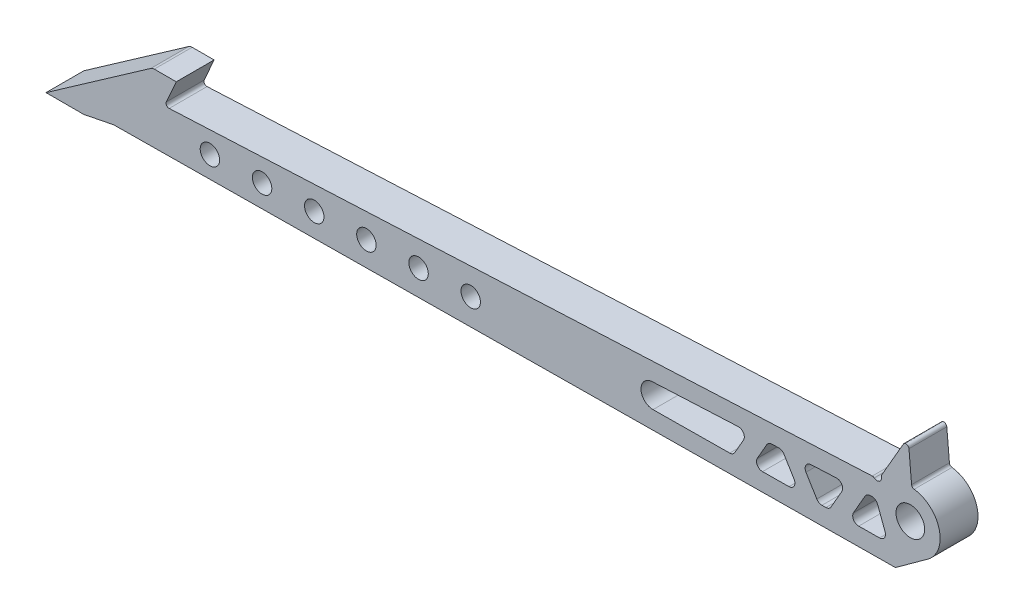
SolidWorks part; units mm, degrees
material "AISI 4340 Steel, normalized"
ref_plane "Front Plane" through (0, 0, 0) normal (0, 0, 1) x (1, 0, 0)
ref_plane "Top Plane" through (0, 0, 0) normal (0, 1, 0) x (1, 0, 0)
ref_plane "Right Plane" through (0, 0, 0) normal (1, 0, 0) x (0, 0, -1)
sketch "Sketch1" plane through (0, 0, 0) normal (0, 0, 1) x (1, 0, 0)
  line L0 (-254.1014, 66.7622) -> (-244.1014, 68.7622)
  line L1 (-254.1014, 66.7622) -> (-266.8014, 66.7622)
  line L2 (-266.8014, 66.7622) -> (-231.0977, 91.7622)
  line L3 (-231.0977, 91.7622) -> (-223.0977, 91.7622)
  line L4 (-223.0977, 91.7622) -> (-227.0977, 82.7622)
  line L5 (-63.3598, 84.4827) -> (11.6902, 88.0244)
  line L6 (-244.1014, 68.7622) -> (18.1986, 71.2622)
  line L7 (18.1986, 71.2622) -> (29.0674, 79.1405)
  line L8 (16.0571, 94.2372) -> (-227.0977, 82.7622)
  line L9 (12.547, 94.0715) -> (22.4576, 111.2372)
  line L10 (11.6902, 88.0244) -> (15.7326, 77.239)
  line L11 (15.7326, 77.239) -> (-63.1331, 76.4873)
  line L12 (22.4576, 111.2372) -> (23.6835, 97.2254)
  line L13 (22.7176, 112.6875) -> (30.656, 126.4372) construction
  line L14 (84.9758, 66.7622) -> (-105.9511, 66.7622) construction
  line L15 (-211.8014, 76.277) -> (-194.3014, 76.7727)
  line L16 (-211.8014, 69.07) -> (-211.8014, 83.4841) construction
  line L17 (-194.3014, 76.7727) -> (-176.8014, 77.2684)
  line L18 (-176.8014, 77.2684) -> (-159.3014, 77.7641)
  line L19 (-159.3014, 77.7641) -> (-141.8014, 78.2598)
  line L20 (-194.3014, 76.7727) -> (-176.8014, 77.2684)
  line L21 (-176.8014, 77.2684) -> (-159.3014, 77.7641)
  line L22 (-159.3014, 77.7641) -> (-141.8014, 78.2598)
  line L23 (-141.8014, 78.2598) -> (-124.3014, 78.7555)
  circle A0 centre (23.1986, 87.2372) radius 10
  circle A1 centre (23.1986, 87.2372) radius 4.8025
  arc A2 (-63.1331, 76.4873) -> (-63.3598, 84.4827) centre (-63.1713, 80.4871) cw
  circle A3 centre (-211.8014, 76.277) radius 3.2639
  circle A4 centre (-176.8014, 77.2684) radius 3.2639
  circle A5 centre (-141.8014, 78.2598) radius 3.2639
  circle A6 centre (-194.3014, 76.7727) radius 3.2639
  circle A7 centre (-159.3014, 77.7641) radius 3.2639
  circle A8 centre (-124.3014, 78.7555) radius 3.2639
  point P33 (-211.8014, 76.277)
  dimension "D1" = 20
  dimension "D19" = 4
  dimension "D20" = 6.5278
  dimension "D28" = 9.605
  dimension "D2" = 12.7
  dimension "D3" = 35
  dimension "D4" = 290
  dimension "D5" = 8
  dimension "D6" = 2
  dimension "D7" = 25
  dimension "D8" = 4
  dimension "D9" = 14
  dimension "D10" = 5
  dimension "D11" = 6
  dimension "D12" = 6
  dimension "D13" = 70
  dimension "D14" = 10.5
  dimension "D15" = 1
  dimension "D16" = 10
  dimension "D17" = 35
  dimension "D18" = 24
  dimension "D21" = 55
  dimension "D22" = 125
  dimension "D23" = 4.5
  dimension "D24" = 7
  dimension "D25" = 66.7622
  dimension "D26" = 87.2372
  dimension "D27" = 23.1986
extrude "Boss-Extrude1" add sketch "Sketch1" along normal blind 12.7
sketch "Sketch2" plane through (0, 0, 12.7) normal (0, 0, 1) x (1, 0, 0)
  line L0 (12.547, 94.0715) -> (12.0276, 94.9261) construction
  line L1 (12.547, 94.0715) -> (-227.0977, 82.7622) construction
  line L2 (12.547, 94.0715) -> (22.4576, 111.2372) construction
  line L3 (12.547, 94.0715) -> (-227.0977, 82.7622) construction
  line L4 (12.547, 94.0715) -> (22.4576, 111.2372) construction
  circle A0 centre (12.0276, 94.9261) radius 1.5
  dimension "D2" = 3
  dimension "D1" = 1
  dimension "D3" = 122.702
  dimension "D4" = 61.409
extrude "Cut-Extrude1" cut sketch "Sketch2" against normal through all
sketch "Sketch3" plane through (0, 0, 12.7) normal (0, 0, 1) x (1, 0, 0)
  line L0 (5.2912, 87.7224) -> (-0.8014, 77.0814)
  line L1 (-10.801, 76.9861) -> (-16.6947, 86.6849)
  line L2 (-10.801, 76.9861) -> (-8.7237, 73.5677)
  line L3 (-0.8014, 77.0814) -> (-2.2921, 74.4779)
  line L4 (5.2912, 87.7224) -> (6.7818, 90.3259)
  line L5 (-16.6947, 86.6849) -> (-18.772, 90.1032)
  line L6 (-27.6947, 86.1658) -> (-33.0722, 76.7738)
  line L7 (-33.0722, 76.7738) -> (-34.5628, 74.1703)
  line L8 (-27.6947, 86.1658) -> (-26.2041, 88.7692)
  line L9 (-5.8012, 77.0337) -> (-6.0788, 106.1603) construction
  line L10 (15.7326, 77.239) -> (-63.1331, 76.4873) construction
  line L11 (-63.3598, 84.4827) -> (11.6902, 88.0244) construction
  circle A0 centre (23.1986, 87.2372) radius 4.8025 construction
  dimension "D1" = 24
  dimension "D2" = 3
  dimension "D3" = 4
  dimension "D4" = 3
  dimension "D5" = 30.74
  dimension "D6" = 5
  dimension "D7" = 11
  dimension "D8" = 11.1938
extrude "Extrude-Thin1" add sketch "Sketch3" against normal up to surface (12.7 mm away) thin up to face at (-121.0375, 78.7555, 0) thin type mid plane wall 5.5
fillet "Fillet1" radius 2 14 edges at (-24.4379, 86.3195, 6.35) (-19.823, 86.5373, 6.35) (-30.9516, 86.0121, 6.35) (8.5481, 87.8761, 6.35) (11.6902, 88.0244, 6.35) (-13.5665, 86.8325, 6.35) (2.0343, 87.5687, 6.35) (-29.8859, 76.8042, 6.35) (-14.0004, 76.9556, 6.35) (-36.2584, 76.7434, 6.35) (2.3848, 77.1117, 6.35) (15.7326, 77.239, 6.35) (-7.6016, 77.0166, 6.35) (-3.9877, 77.051, 6.35)
fillet "Fillet2" radius 1 2 edges at (10.8542, 93.9916, 6.35) (13.3956, 95.5413, 6.35)
fillet "Fillet3" radius 1 1 edges at (-227.0977, 82.7622, 6.35)
fillet "Fillet4" radius 2 1 edges at (-231.0977, 91.7622, 6.35)
fillet "Fillet5" radius 1 2 edges at (23.6835, 97.2254, 6.35) (22.4576, 111.2372, 6.35)
equation "\"D4@Sketch2\"=\"D3@Sketch2\"/2"
